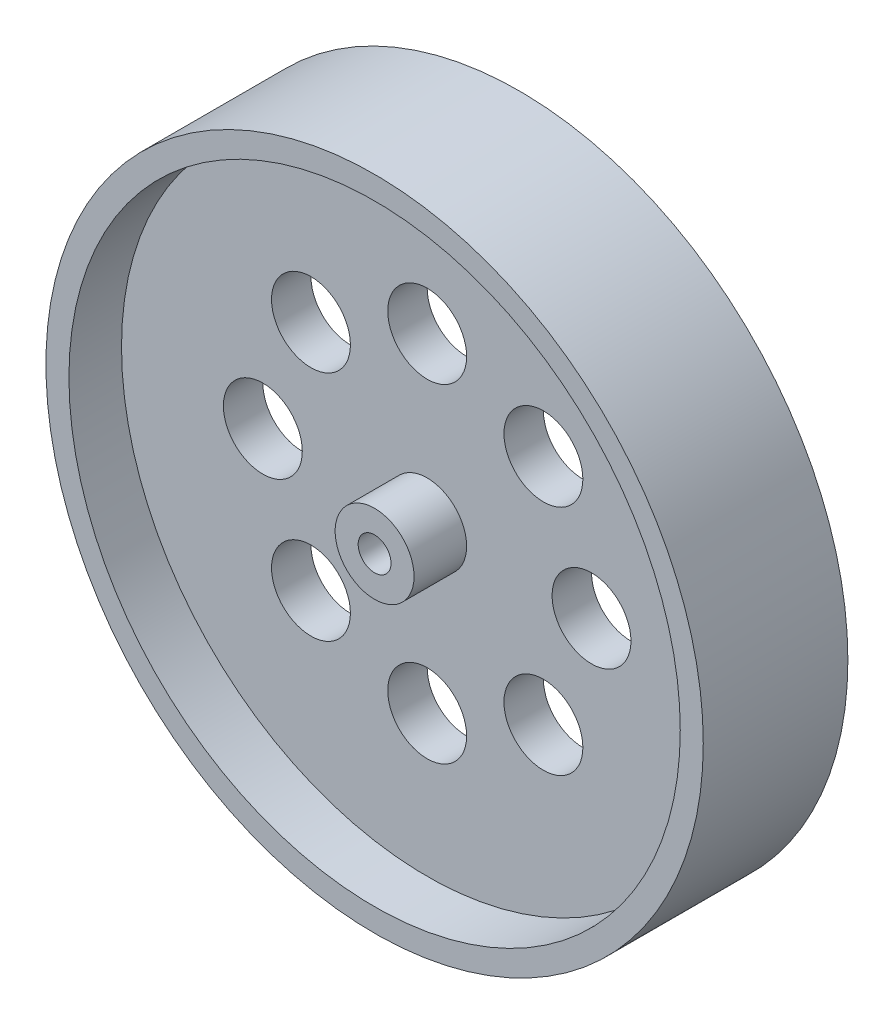
SolidWorks part; units mm, degrees
ref_plane "Plan de face" through (0, 0, 0) normal (0, 0, 1) x (1, 0, 0)
ref_plane "Plan de dessus" through (0, 0, 0) normal (0, 1, 0) x (1, 0, 0)
ref_plane "Plan de droite" through (0, 0, 0) normal (1, 0, 0) x (0, 0, -1)
sketch "Esquisse1" plane through (0, 0, 0) normal (0, 0, 1) x (1, 0, 0)
  circle A0 centre (0, 0) radius 50
extrude "Boss.-Extru.1" add sketch "Esquisse1" along normal blind 22
sketch "Esquisse2" plane through (0, 0, 22) normal (0, 0, 1) x (1, 0, 0)
  circle A0 centre (0, 0) radius 2.5
extrude "Enlèv. mat.-Extru.1" cut sketch "Esquisse2" against normal blind 7
sketch "Esquisse4" plane through (0, 0, 0) normal (0, 0, -1) x (-1, 0, 0)
  line L0 (-1.8698, 1.6595) -> (-2.4963, -0.1353)
  circle A0 centre (0, 0) radius 2.5
extrude "Enlèv. mat.-Extru.2" cut sketch "Esquisse4" against normal blind 15 contours L0 A0
sketch "Esquisse5" plane through (0, 0, 0) normal (0, 0, -1) x (-1, 0, 0)
  circle A0 centre (0, 0) radius 6
  circle A1 centre (0, 0) radius 46.5
extrude "Enlèv. mat.-Extru.3" cut sketch "Esquisse5" against normal blind 8
sketch "Esquisse7" plane through (0, 0, 22) normal (0, 0, 1) x (1, 0, 0)
  circle A0 centre (0, 0) radius 6
  circle A1 centre (0, 0) radius 46.5
extrude "Enlèv. mat.-Extru.4" cut sketch "Esquisse7" against normal blind 8
sketch "Esquisse8" plane through (0, 0, 8) normal (0, 0, -1) x (-1, 0, 0)
  circle A0 centre (-25, 0) radius 6
  point P2 (0, 0)
extrude "Enlèv. mat.-Extru.5" cut sketch "Esquisse8" against normal blind 8
sketch "Esquisse9" plane through (0, 0, 8) normal (0, 0, -1) x (-1, 0, 0)
  circle A0 centre (0, 25) radius 6
  point P2 (0, 0)
extrude "Enlèv. mat.-Extru.6" cut sketch "Esquisse9" against normal blind 8
sketch "Esquisse10" plane through (0, 0, 8) normal (0, 0, -1) x (-1, 0, 0)
  circle A0 centre (25, 0) radius 6
extrude "Enlèv. mat.-Extru.7" cut sketch "Esquisse10" against normal blind 8
sketch "Esquisse11" plane through (0, 0, 8) normal (0, 0, -1) x (-1, 0, 0)
  circle A0 centre (0, -25) radius 6
  point P2 (0, 0)
extrude "Enlèv. mat.-Extru.8" cut sketch "Esquisse11" against normal blind 8
sketch "Esquisse12" plane through (0, 0, 8) normal (0, 0, -1) x (-1, 0, 0)
  circle A0 centre (-17.68, 17.68) radius 6
  point P2 (0, 0)
extrude "Enlèv. mat.-Extru.10" cut sketch "Esquisse12" against normal blind 8
sketch "Esquisse13" plane through (0, 0, 8) normal (0, 0, -1) x (-1, 0, 0)
  circle A0 centre (17.68, 17.68) radius 6
  point P2 (0, 0)
extrude "Enlèv. mat.-Extru.11" cut sketch "Esquisse13" against normal blind 8
sketch "Esquisse14" plane through (0, 0, 8) normal (0, 0, -1) x (-1, 0, 0)
  circle A0 centre (-17.68, -17.68) radius 6
extrude "Enlèv. mat.-Extru.12" cut sketch "Esquisse14" against normal blind 8
sketch "Esquisse15" plane through (0, 0, 8) normal (0, 0, -1) x (-1, 0, 0)
  circle A0 centre (17.68, -17.68) radius 6
  point P2 (0, 0)
extrude "Enlèv. mat.-Extru.13" cut sketch "Esquisse15" against normal blind 8
